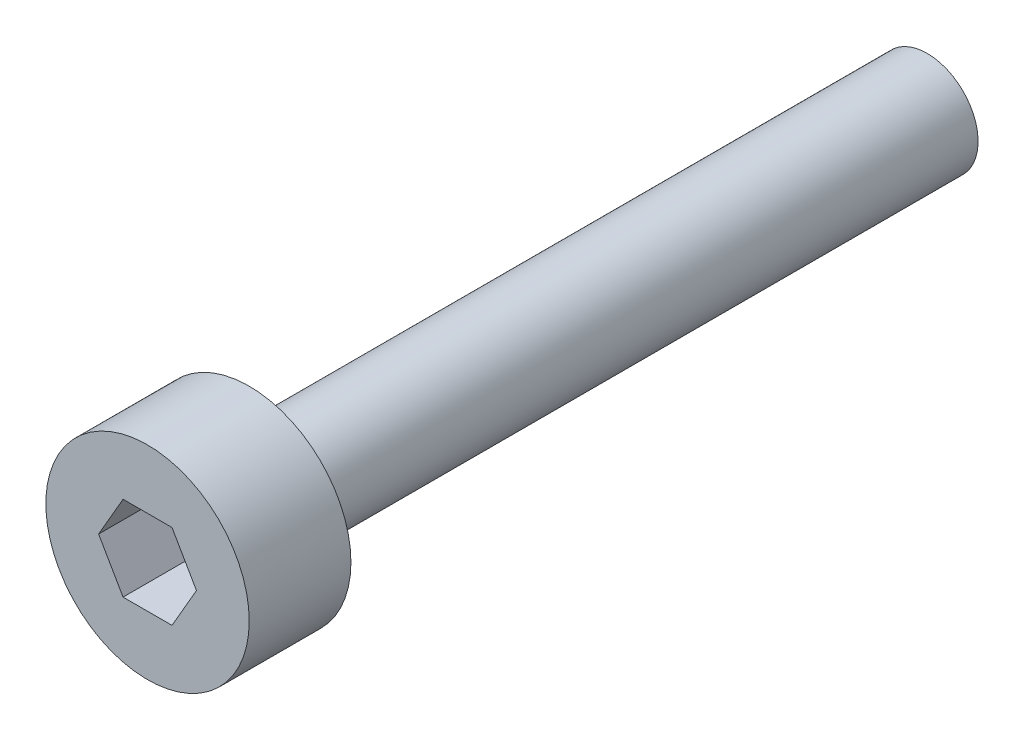
SolidWorks part; units mm, degrees
ref_plane "正面" through (0, 0, 0) normal (0, 0, 1) x (1, 0, 0)
ref_plane "平面" through (0, 0, 0) normal (0, 1, 0) x (1, 0, 0)
ref_plane "右側面" through (0, 0, 0) normal (1, 0, 0) x (0, 0, -1)
sketch "ｽｹｯﾁ5" plane through (0, 0, 0) normal (0, 0, 1) x (1, 0, 0)
  circle A0 centre (0, 0) radius 3
  dimension "D1" = 6
extrude "ﾎﾞｽ - 押し出し1" add sketch "ｽｹｯﾁ5" along normal blind 3
sketch "ｽｹｯﾁ6" plane through (0, 0, 3) normal (0, 0, 1) x (1, 0, 0)
  line L1 (1.4434, 0) -> (0.7217, 1.25)
  line L2 (0.7217, 1.25) -> (-0.7217, 1.25)
  line L3 (-0.7217, 1.25) -> (-1.4434, 0)
  line L4 (-1.4434, 0) -> (-0.7217, -1.25)
  line L5 (-0.7217, -1.25) -> (0.7217, -1.25)
  line L6 (0.7217, -1.25) -> (1.4434, 0)
  circle A0 centre (0, 0) radius 1.25 construction
  dimension "D1" = 2.5
extrude "ｶｯﾄ - 押し出し1" cut sketch "ｽｹｯﾁ6" against normal blind 2
sketch "ｽｹｯﾁ7" plane through (0, 0, 0) normal (0, 0, -1) x (-1, 0, 0)
  circle A0 centre (0, 0) radius 1.5
  dimension "D1" = 3
extrude "ﾎﾞｽ - 押し出し2" add sketch "ｽｹｯﾁ7" along normal blind 20
